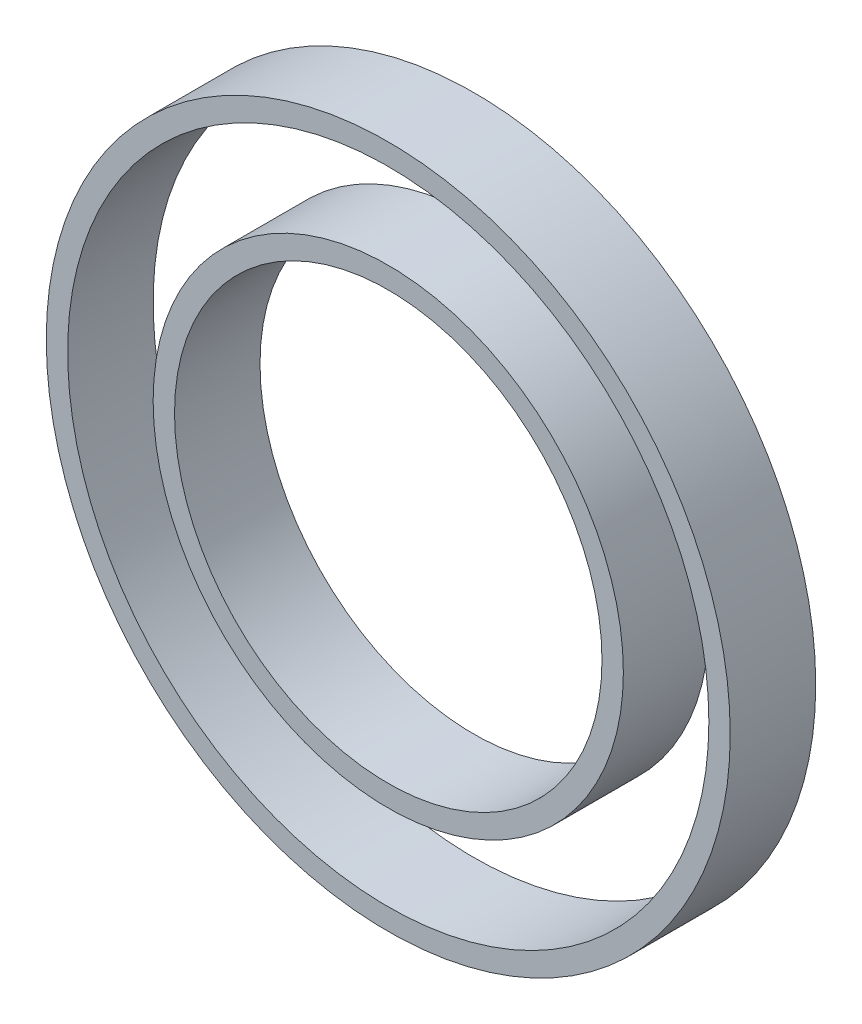
SolidWorks part; units mm, degrees
ref_plane "Front Plane" through (0, 0, 0) normal (0, 0, 1) x (1, 0, 0)
ref_plane "Top Plane" through (0, 0, 0) normal (0, 1, 0) x (1, 0, 0)
ref_plane "Right Plane" through (0, 0, 0) normal (1, 0, 0) x (0, 0, -1)
sketch "Sketch1" plane through (0, 0, 0) normal (0, 0, 1) x (1, 0, 0)
  circle A0 centre (0, 0) radius 5
  circle A1 centre (0, 0) radius 5.5
  circle A2 centre (0, 0) radius 7.5
  circle A3 centre (0, 0) radius 8
extrude "Boss-Extrude1" add sketch "Sketch1" along normal blind 2 contours A3 A2 | A1 A0
